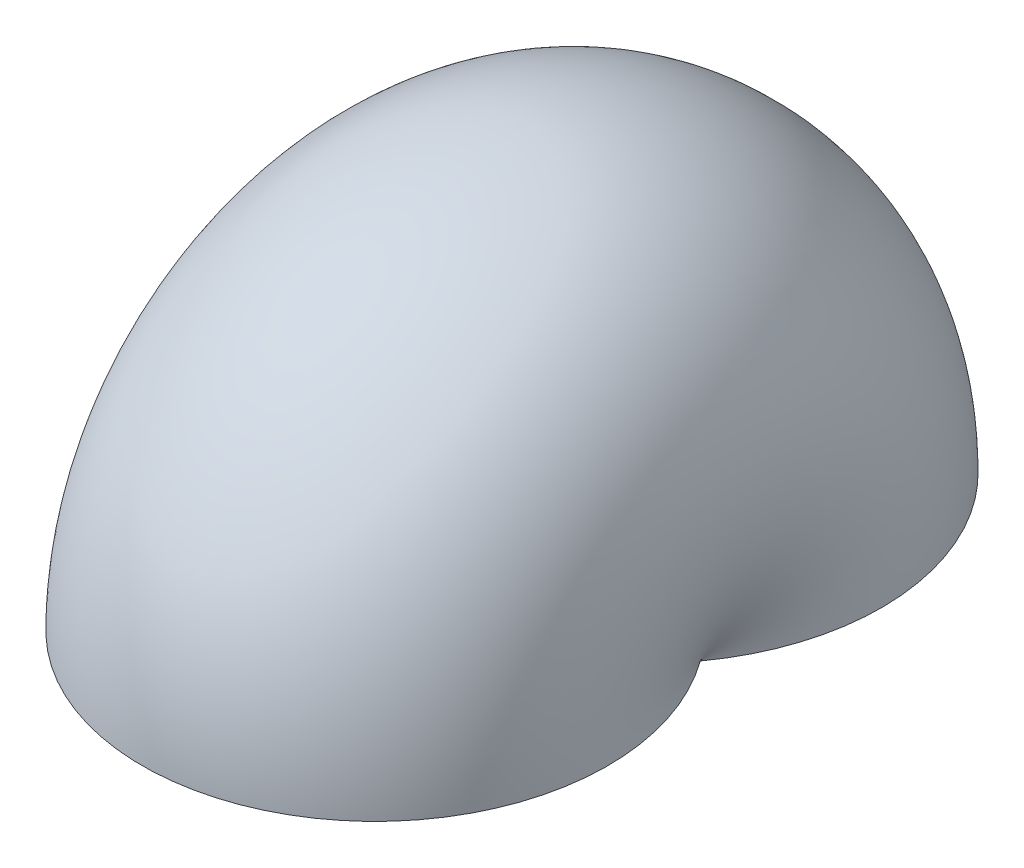
SolidWorks part; units mm, degrees
ref_plane "Front Plane" through (0, 0, 0) normal (0, 0, 1) x (1, 0, 0)
ref_plane "Top Plane" through (0, 0, 0) normal (0, 1, 0) x (1, 0, 0)
ref_plane "Right Plane" through (0, 0, 0) normal (1, 0, 0) x (0, 0, -1)
sketch "Sketch1" plane through (0, 0, 0) normal (0, 1, 0) x (1, 0, 0)
  line L0 (-109.8952, 80) -> (109.8952, 80) construction
  arc A0 (-109.8952, 80) -> (109.8952, 80) centre (0, 0) ccw
  circle A1 centre (0, 160) radius 135.93
  dimension "D1" = 271.86
  dimension "D2" = 160
revolve "Revolve14" add sketch "Sketch1" angle 180 about L0
sketch "Sketch3" plane through (0, 0, 0) normal (0, -1, 0) x (1, 0, 0)
  line L0 (-109.8952, -80) -> (109.8952, -80) construction
  arc A0 (-109.8952, -80) -> (109.8952, -80) centre (0, 0) ccw
revolve "Cut-Revolve1" cut sketch "Sketch3" angle 360 about L0
